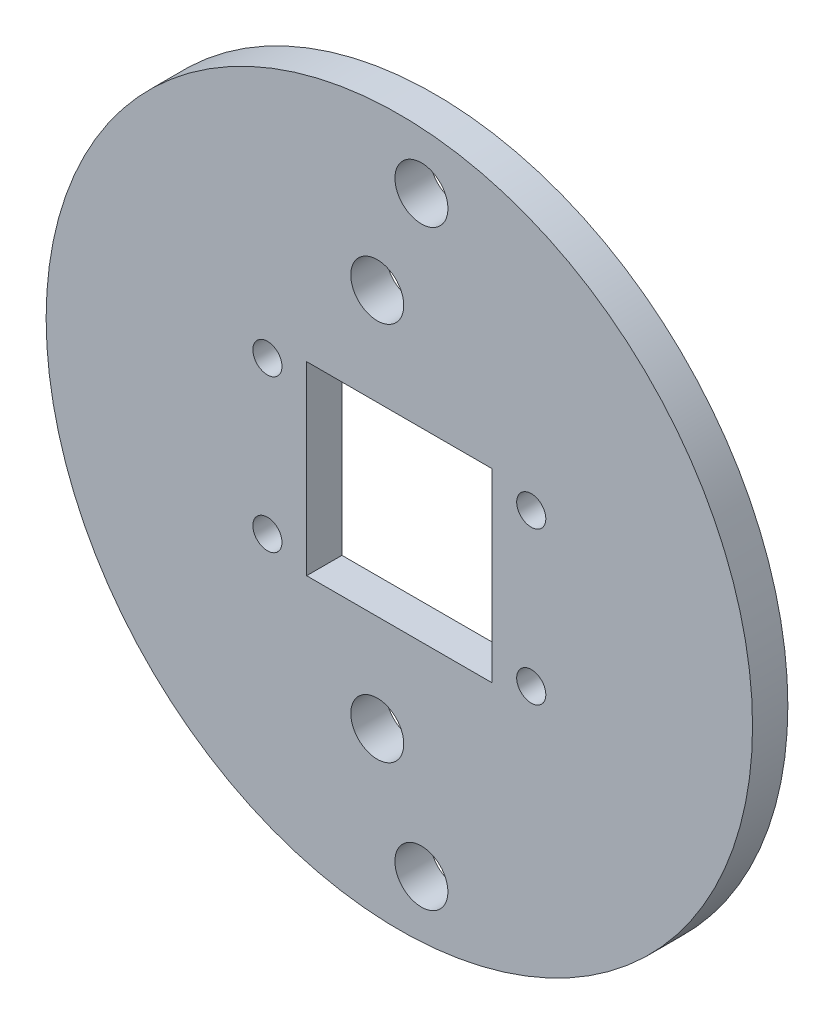
SolidWorks part; units mm, degrees
ref_plane "前视基准面" through (0, 0, 0) normal (0, 0, 1) x (1, 0, 0)
ref_plane "上视基准面" through (0, 0, 0) normal (0, 1, 0) x (1, 0, 0)
ref_plane "右视基准面" through (0, 0, 0) normal (1, 0, 0) x (0, 0, -1)
other "Configuration Table"
sketch "草图1" plane through (0, 0, 0) normal (0, 0, 1) x (1, 0, 0)
  line L0 (0, 10.5) -> (0, 25.6787) construction
  line L1 (-10.5, 10.5) -> (10.5, 10.5)
  line L2 (-10.5, 10.5) -> (-10.5, -10.5)
  line L3 (-10.5, -10.5) -> (10.5, -10.5)
  line L4 (10.5, 10.5) -> (10.5, -10.5)
  line L5 (-10.5, 10.5) -> (10.5, -10.5) construction
  line L6 (-10.5, -10.5) -> (10.5, 10.5) construction
  line L7 (0, 0) -> (14.9389, 0) construction
  circle A0 centre (0, 0) radius 40
  circle A1 centre (0, 0) radius 17.25 construction
  circle A3 centre (14.9389, 8.625) radius 1.65
  circle A4 centre (14.9389, -8.625) radius 1.65
  circle A6 centre (-14.9389, -8.625) radius 1.65
  circle A7 centre (-14.9389, 8.625) radius 1.65
  circle A9 centre (2.5, 33.5) radius 3
  circle A10 centre (-2.5, 21.5) radius 3
  circle A11 centre (-2.5, -21.5) radius 3
  circle A12 centre (2.5, -33.5) radius 3
  point P18 (0, 0)
  point P24 (14.9389, 0)
  dimension "D1" = 80
  dimension "D2" = 34.5
  dimension "D3" = 11
  dimension "D7" = 12
  dimension "D4" = 6
  dimension "D8" = 6
  dimension "D5" = 21
  dimension "D6" = 21
  dimension "D9" = 5
  dimension "D10" = 2.5
extrude "凸台-拉伸1" add sketch "草图1" along normal blind 4
